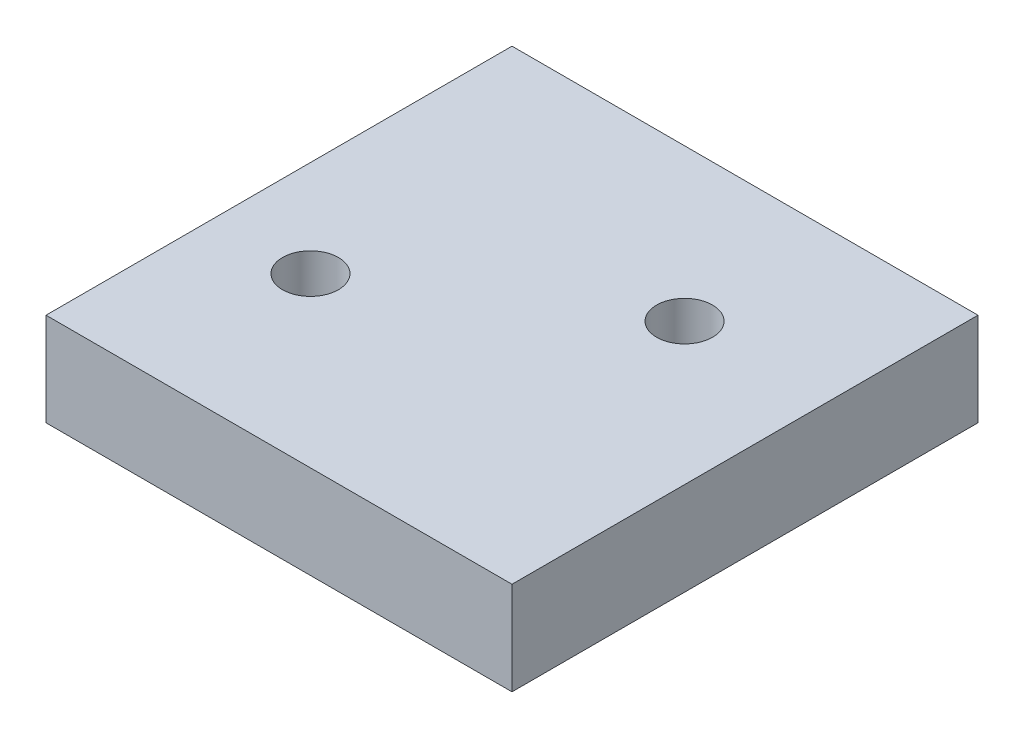
SolidWorks part; units mm, degrees
ref_plane "Front Plane" through (0, 0, 0) normal (0, 0, 1) x (1, 0, 0)
ref_plane "Top Plane" through (0, 0, 0) normal (0, 1, 0) x (1, 0, 0)
ref_plane "Right Plane" through (0, 0, 0) normal (1, 0, 0) x (0, 0, -1)
sketch "Sketch1" plane through (0, 0, 0) normal (0, 1, 0) x (1, 0, 0)
  line L1 (0, 0) -> (100, 0)
  line L2 (0, 0) -> (0, 100)
  line L3 (0, 100) -> (100, 100)
  line L4 (100, 0) -> (100, 100)
  dimension "D1" = 100
  dimension "D2" = 100
extrude "Boss-Extrude1" add sketch "Sketch1" along normal blind 20
hole_wizard "Ø12.0 (12) Diameter Hole1" positions "Sketch2" profile "Sketch3" hole size "Ø12.0" standard "ISO" end condition through all
sketch "Sketch2" plane through (0, 20, 0) normal (0, 1, 0) x (1, 0, 0)
  point P0 (69.6216, 67.4065)
  point P2 (20.648, 36.103)
sketch "Sketch3" plane through (69.6216, 20, -67.4065) normal (1, 0, 0) x (0, 0, 1)
  line L0 (0, 0) -> (0, 20)
  line L1 (0, 20) -> (6, 20)
  line L2 (6, 20) -> (6, 0)
  line L5 (6, 0) -> (0, 0)
  line L11 (0, -6.35) -> (0, 107.95) construction
  dimension "Thru Hole Dia." = 12
  dimension "Thru Hole Depth" = 20
